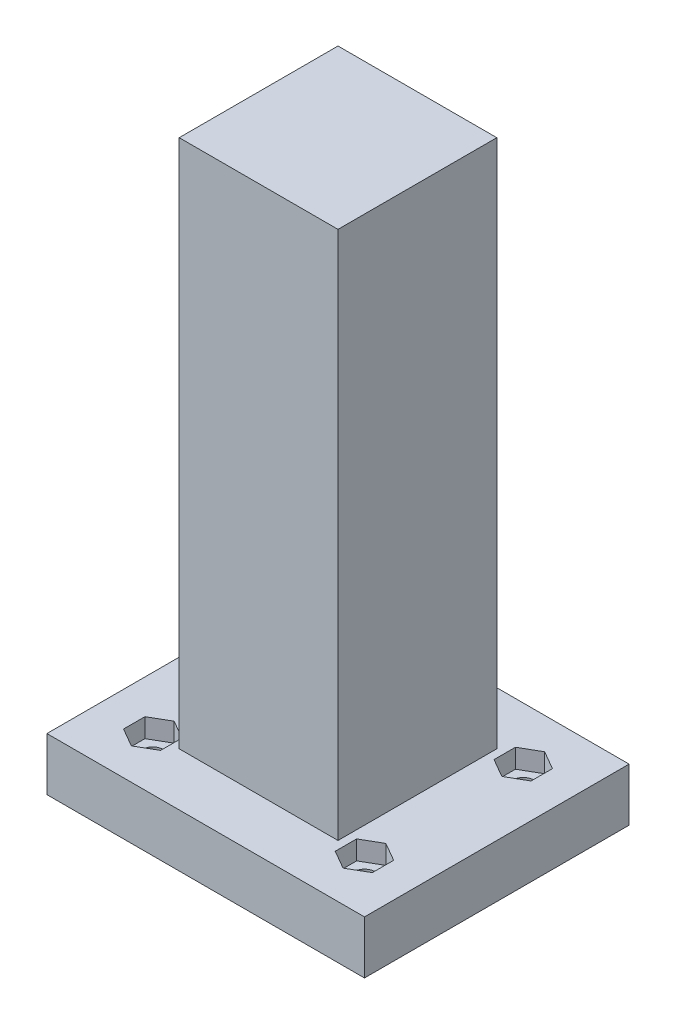
SolidWorks part; units mm, degrees
ref_plane "Front Plane" through (0, 0, 0) normal (0, 0, 1) x (1, 0, 0)
ref_plane "Top Plane" through (0, 0, 0) normal (0, 1, 0) x (1, 0, 0)
ref_plane "Right Plane" through (0, 0, 0) normal (1, 0, 0) x (0, 0, -1)
sketch "Sketch1" plane through (0, 0, 0) normal (0, 1, 0) x (1, 0, 0)
  line L0 (30, 0) -> (30, -50) construction
  line L1 (0, 0) -> (60, 0)
  line L2 (0, 0) -> (0, -50)
  line L3 (0, -50) -> (60, -50)
  line L4 (60, 0) -> (60, -50)
  line L5 (60, -25) -> (0, -25) construction
  point P9 (0, 0)
  dimension "D1" = 50
  dimension "D2" = 60
extrude "Boss-Extrude1" add sketch "Sketch1" along normal blind 10
sketch "Sketch2" plane through (0, 10, 0) normal (0, 1, 0) x (1, 0, 0)
  line L0 (30, 0) -> (30, -50) construction
  line L1 (60, 0) -> (0, 0) construction
  line L3 (60, -50) -> (60, 0) construction
  circle A0 centre (50, -10) radius 2
  circle A1 centre (10, -10) radius 2
  circle A5 centre (10, -40) radius 2
  circle A7 centre (50, -40) radius 2
  circle A9 centre (30, -25) radius 2
  dimension "D3" = 4
  dimension "D5" = 4
  dimension "D1" = 10
  dimension "D2" = 10
  dimension "D4" = 2
extrude "Cut-Extrude1" cut sketch "Sketch2" against normal through all
sketch "Sketch3" plane through (0, 10, 0) normal (0, 1, 0) x (1, 0, 0)
  line L25 (10, -35.9585) -> (6.5, -37.9793)
  line L26 (6.5, -37.9793) -> (6.5, -42.0207)
  line L27 (6.5, -42.0207) -> (10, -44.0415)
  line L28 (10, -44.0415) -> (13.5, -42.0207)
  line L29 (13.5, -42.0207) -> (13.5, -37.9793)
  line L30 (13.5, -37.9793) -> (10, -35.9585)
  line L31 (50, -35.9585) -> (46.5, -37.9793)
  line L32 (46.5, -37.9793) -> (46.5, -42.0207)
  line L33 (46.5, -42.0207) -> (50, -44.0415)
  line L34 (50, -44.0415) -> (53.5, -42.0207)
  line L35 (53.5, -42.0207) -> (53.5, -37.9793)
  line L36 (53.5, -37.9793) -> (50, -35.9585)
  line L37 (50, -5.9585) -> (46.5, -7.9793)
  line L38 (46.5, -7.9793) -> (46.5, -12.0207)
  line L39 (46.5, -12.0207) -> (50, -14.0415)
  line L40 (50, -14.0415) -> (53.5, -12.0207)
  line L41 (53.5, -12.0207) -> (53.5, -7.9793)
  line L42 (53.5, -7.9793) -> (50, -5.9585)
  line L43 (10, -5.9585) -> (6.5, -7.9793)
  line L44 (6.5, -7.9793) -> (6.5, -12.0207)
  line L45 (6.5, -12.0207) -> (10, -14.0415)
  line L46 (10, -14.0415) -> (13.5, -12.0207)
  line L47 (13.5, -12.0207) -> (13.5, -7.9793)
  line L48 (13.5, -7.9793) -> (10, -5.9585)
  circle A0 centre (10, -40) radius 3.5 construction
  circle A1 centre (50, -40) radius 3.5 construction
  circle A2 centre (50, -10) radius 3.5 construction
  circle A3 centre (10, -10) radius 3.5 construction
  dimension "D1" = 7
  dimension "D2" = 2
extrude "Cut-Extrude2" cut sketch "Sketch3" against normal blind 3.6
sketch "Sketch4" plane through (0, 10, 0) normal (0, 1, 0) x (1, 0, 0)
  line L5 (30, 0) -> (30, -50) construction
  line L7 (15, -40) -> (45, -40)
  line L8 (15, -40) -> (15, -10)
  line L9 (15, -10) -> (45, -10)
  line L10 (45, -40) -> (45, -10)
  line L11 (15, -40) -> (45, -10) construction
  line L12 (15, -10) -> (45, -40) construction
  point P0 (30, -25)
  dimension "D1" = 30
  dimension "D2" = 30
extrude "Boss-Extrude2" add sketch "Sketch4" along normal blind 100 contours L9 L10 L7 L8
sketch "Sketch6" plane through (0, 10, 0) normal (0, -1, 0) x (1, 0, 0)
  line L0 (30, 0) -> (30, 50) construction
  circle A0 centre (30, 25) radius 2
extrude "Cut-Extrude5" cut sketch "Sketch6" against normal blind 30
